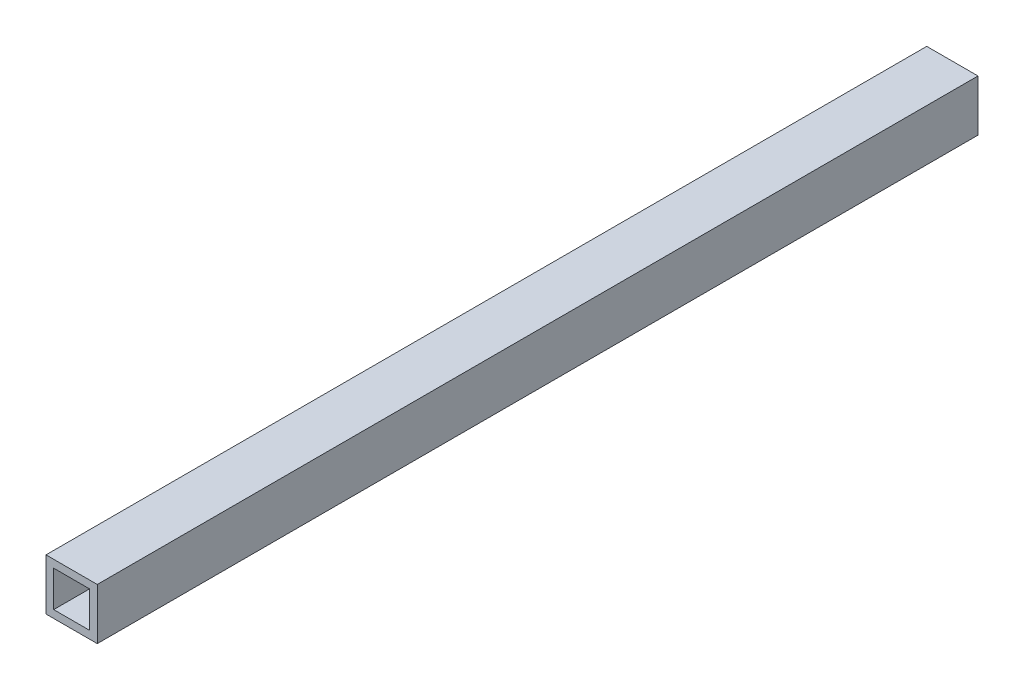
SolidWorks part; units mm, degrees
ref_plane "Front Plane" through (0, 0, 0) normal (0, 0, 1) x (1, 0, 0)
ref_plane "Top Plane" through (0, 0, 0) normal (0, 1, 0) x (1, 0, 0)
ref_plane "Right Plane" through (0, 0, 0) normal (1, 0, 0) x (0, 0, -1)
sketch "Sketch1" plane through (0, 0, 0) normal (0, 0, 1) x (1, 0, 0)
  line L1 (-5, 5) -> (5, 5)
  line L2 (-5, 5) -> (-5, -5)
  line L3 (-5, -5) -> (5, -5)
  line L4 (5, 5) -> (5, -5)
  line L5 (-5, 5) -> (5, -5) construction
  line L6 (-5, -5) -> (5, 5) construction
  line L7 (-3.5, -3.5) -> (3.5, -3.5)
  line L8 (-3.5, -3.5) -> (-3.5, 3.5)
  line L9 (-3.5, 3.5) -> (3.5, 3.5)
  line L10 (3.5, -3.5) -> (3.5, 3.5)
  line L11 (-3.5, -3.5) -> (3.5, 3.5) construction
  line L12 (-3.5, 3.5) -> (3.5, -3.5) construction
  point P0 (0, 0)
  point P6 (0, 0)
  dimension "D1" = 10
  dimension "D2" = 10
  dimension "D3" = 1.5
extrude "Boss-Extrude1" add sketch "Sketch1" along normal blind 171.8
